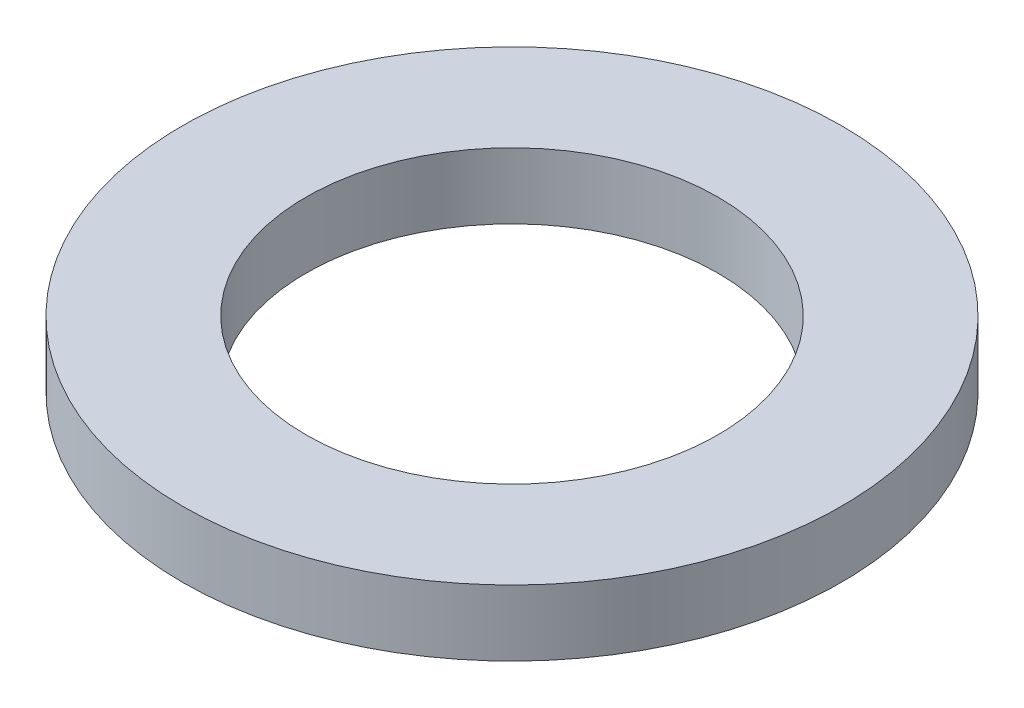
SolidWorks part; units mm, degrees
ref_plane "前视基准面" through (0, 0, 0) normal (0, 0, 1) x (1, 0, 0)
ref_plane "上视基准面" through (0, 0, 0) normal (0, 1, 0) x (1, 0, 0)
ref_plane "右视基准面" through (0, 0, 0) normal (1, 0, 0) x (0, 0, -1)
other "Configuration Table"
sketch "草图1" plane through (0, 0, 0) normal (0, 1, 0) x (1, 0, 0)
  circle A0 centre (0, 0) radius 2.5
  circle A1 centre (0, 0) radius 4
  dimension "D1" = 5
  dimension "D2" = 8
extrude "凸台-拉伸1" add sketch "草图1" along normal blind 0.8 contours A1 | A0
